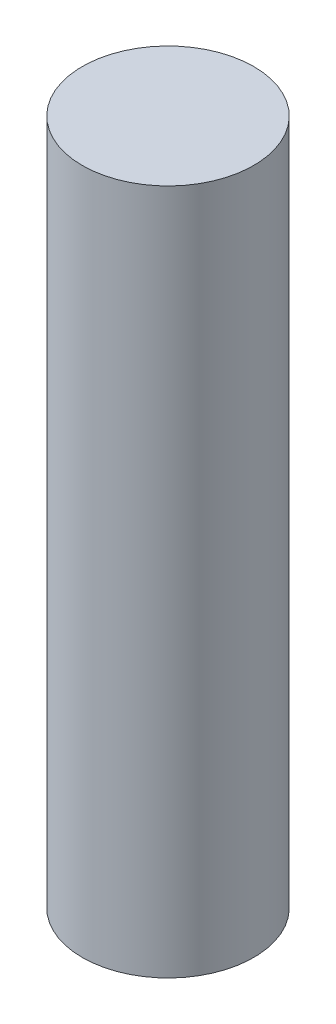
SolidWorks part; units mm, degrees
ref_plane "前视基准面" through (0, 0, 0) normal (0, 0, 1) x (1, 0, 0)
ref_plane "上视基准面" through (0, 0, 0) normal (0, 1, 0) x (1, 0, 0)
ref_plane "右视基准面" through (0, 0, 0) normal (1, 0, 0) x (0, 0, -1)
sketch "草图1" plane through (0, 0, 0) normal (0, 1, 0) x (1, 0, 0)
  circle A0 centre (0, 0) radius 1.5
  dimension "D1" = 3
extrude "凸台-拉伸1" add sketch "草图1" along normal blind 12
